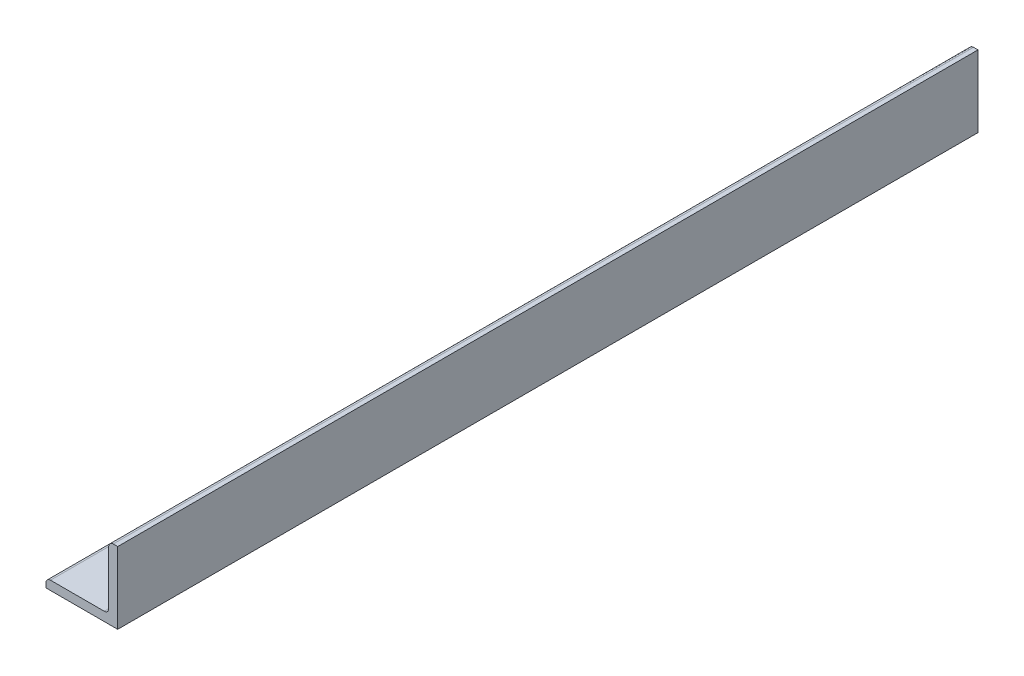
SolidWorks part; units mm, degrees
ref_plane "Front Plane" through (0, 0, 0) normal (0, 0, 1) x (1, 0, 0)
ref_plane "Top Plane" through (0, 0, 0) normal (0, 1, 0) x (1, 0, 0)
ref_plane "Right Plane" through (0, 0, 0) normal (1, 0, 0) x (0, 0, -1)
sketch "Sketch2" plane through (0, 0, 0) normal (0, 0, 1) x (1, 0, 0)
  line L0 (-12.7, 0) -> (12.7, 0)
  line L1 (12.7, 0) -> (12.7, 25.4)
  line L2 (12.7, 25.4) -> (9.525, 25.4) construction
  line L3 (9.525, 23.8125) -> (9.525, 4.7625)
  line L4 (7.9375, 3.175) -> (-11.1125, 3.175)
  line L5 (-12.7, 0) -> (-12.7, 3.175) construction
  line L6 (11.1125, 25.4) -> (12.7, 25.4)
  line L7 (-12.7, 1.5875) -> (-12.7, 0)
  arc A0 (9.525, 23.8125) -> (11.1125, 25.4) centre (11.1125, 23.8125) cw
  arc A1 (-12.7, 1.5875) -> (-11.1125, 3.175) centre (-11.1125, 1.5875) cw
  arc A2 (9.525, 4.7625) -> (7.9375, 3.175) centre (7.9375, 4.7625) cw
  dimension "Vert" = 25.4
  dimension "Horz" = 25.4
  dimension "Thickness" = 3.175
extrude "Boss-Extrude1" add sketch "Sketch2" along normal mid plane 304.8
ref_plane "Contact Plane 1" through (0, 3.175, 0) normal (0, 1, 0) x (1, 0, 0)
ref_plane "Contact Plane 2" through (9.525, 0, 0) normal (-1, 0, 0) x (0, 0, 1)
